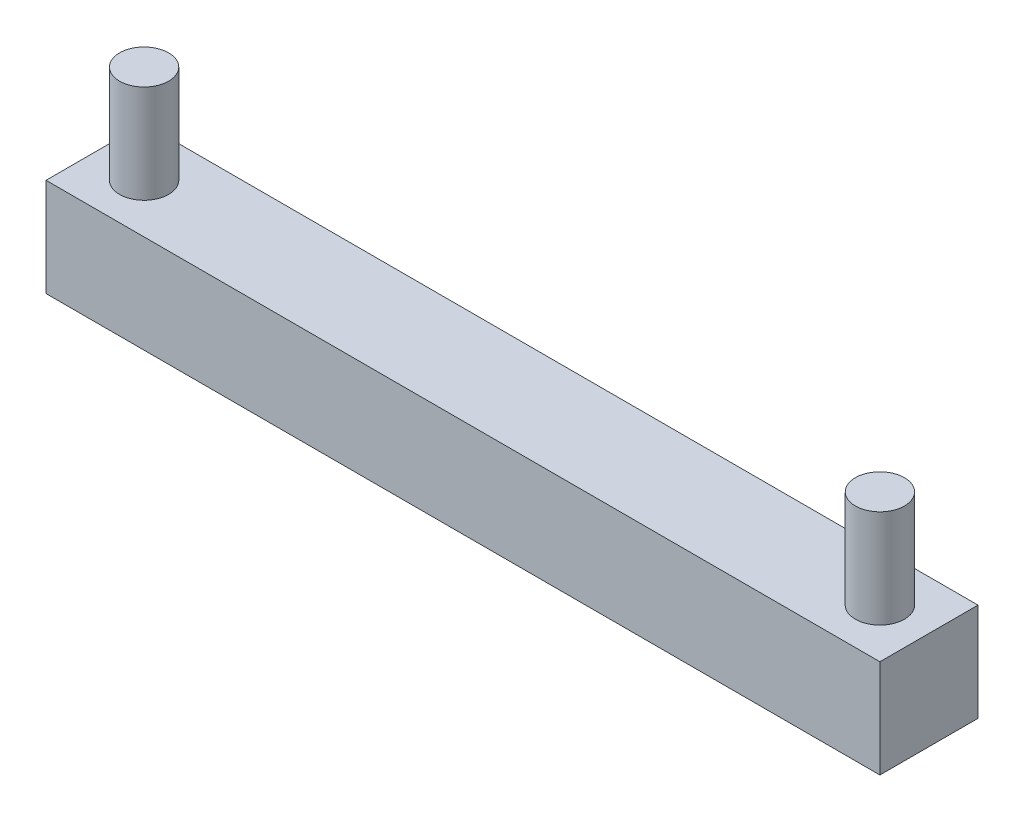
SolidWorks part; units mm, degrees
ref_plane "Plan de face" through (0, 0, 0) normal (0, 0, 1) x (1, 0, 0)
ref_plane "Plan de dessus" through (0, 0, 0) normal (0, 1, 0) x (1, 0, 0)
ref_plane "Plan de droite" through (0, 0, 0) normal (1, 0, 0) x (0, 0, -1)
sketch "Esquisse1" plane through (0, 0, 0) normal (0, 1, 0) x (1, 0, 0)
  line L1 (0, 0) -> (85, 0)
  line L2 (0, 0) -> (0, -10)
  line L3 (0, -10) -> (85, -10)
  line L4 (85, 0) -> (85, -10)
  point P5 (42.5, 0)
  dimension "D1" = 85
  dimension "D2" = 10
extrude "Boss.-Extru.1" add sketch "Esquisse1" along normal blind 10
sketch "Esquisse2" plane through (0, 10, 0) normal (0, 1, 0) x (1, 0, 0)
  line L0 (0, -5) -> (85, -5) construction
  line L1 (0, 0) -> (0, -10) construction
  line L2 (85, -10) -> (85, 0) construction
  circle A0 centre (5, -5) radius 2.5
  circle A1 centre (80, -5) radius 2.5
  dimension "D2" = 5
  dimension "D4" = 5
  dimension "D1" = 5
  dimension "D3" = 5
extrude "Boss.-Extru.2" add sketch "Esquisse2" along normal blind 10
sketch "Esquisse3" plane through (0, 20, 0) normal (0, 1, 0) x (1, 0, 0)
  circle A0 centre (5, -5) radius 2.5
